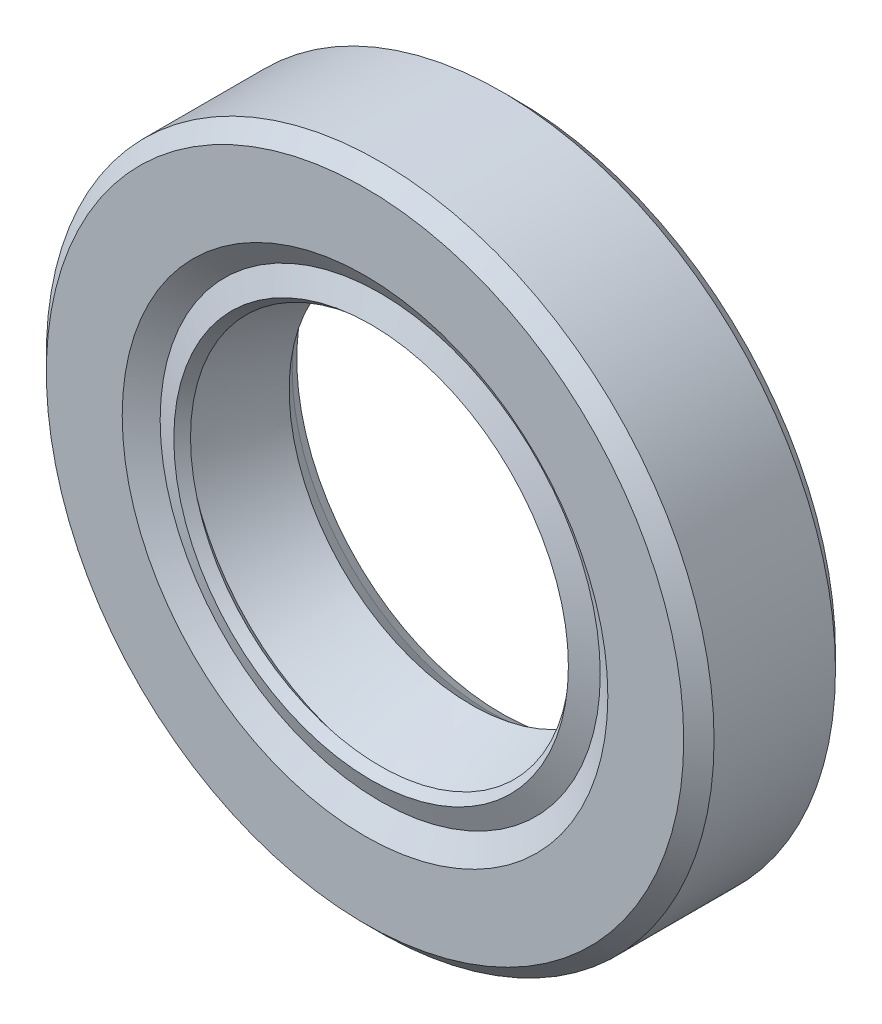
SolidWorks part; units mm, degrees
material "Caoutchouc"
ref_plane "Plan de face" through (0, 0, 0) normal (0, 0, 1) x (1, 0, 0)
ref_plane "Plan de dessus" through (0, 0, 0) normal (0, 1, 0) x (1, 0, 0)
ref_plane "Plan de droite" through (0, 0, 0) normal (1, 0, 0) x (0, 0, -1)
sketch "Esquisse1" plane through (0, 0, 0) normal (1, 0, 0) x (0, 0, -1)
  line L0 (0, 0) -> (18.5167, 0) construction
  line L1 (3.7367, 7.3) -> (4.5, 7.1)
  line L42 (0, 8) -> (0.5, 7.25)
  line L43 (0.5, 7.25) -> (0.2, 6.5)
  line L44 (0.2, 6.5) -> (0.5, 6.25)
  line L45 (0.5, 6.25) -> (1.1, 7)
  line L48 (1.1, 7) -> (3.5, 6)
  line L49 (3.5, 6) -> (4.1, 6.5)
  line L50 (4.1, 6.5) -> (4.5, 6.75)
  line L51 (4.5, 6.75) -> (4.5, 7.1)
  line L55 (1.8835, 8.05) -> (1, 8.6)
  line L56 (1, 8.6) -> (1, 10)
  line L57 (1, 10) -> (5, 10)
  line L58 (5, 10) -> (5, 10.5)
  line L59 (5, 10.5) -> (4.5, 11)
  line L60 (4.5, 11) -> (0.5, 11)
  line L61 (0.5, 11) -> (0, 10.5)
  line L62 (0, 10.5) -> (0, 8)
  arc A5 (3.7367, 7.3) -> (1.8835, 8.05) centre (2.8, 7.65) ccw
  dimension "D22" = 1
  dimension "D1" = 12
  dimension "D2" = 13
  dimension "D3" = 12.5
  dimension "D4" = 45
  dimension "D5" = 0.5
  dimension "D6" = 5
  dimension "D7" = 4.5
  dimension "D8" = 22
  dimension "D9" = 20
  dimension "D10" = 1
  dimension "D11" = 14
  dimension "D12" = 16
  dimension "D13" = 13
  dimension "D14" = 13.5
  dimension "D15" = 0.2
  dimension "D16" = 14.5
  dimension "D17" = 0.5
  dimension "D18" = 0.5
  dimension "D19" = 1.1
  dimension "D20" = 3.5
  dimension "D21" = 4.1
  dimension "D23" = 2.8
  dimension "D24" = 15.3
  dimension "D25" = 16.1
  dimension "D26" = 17.2
  dimension "D27" = 14.6
  dimension "D28" = 14.2
revolve "Révolution1" add sketch "Esquisse1" angle 360 about L0
